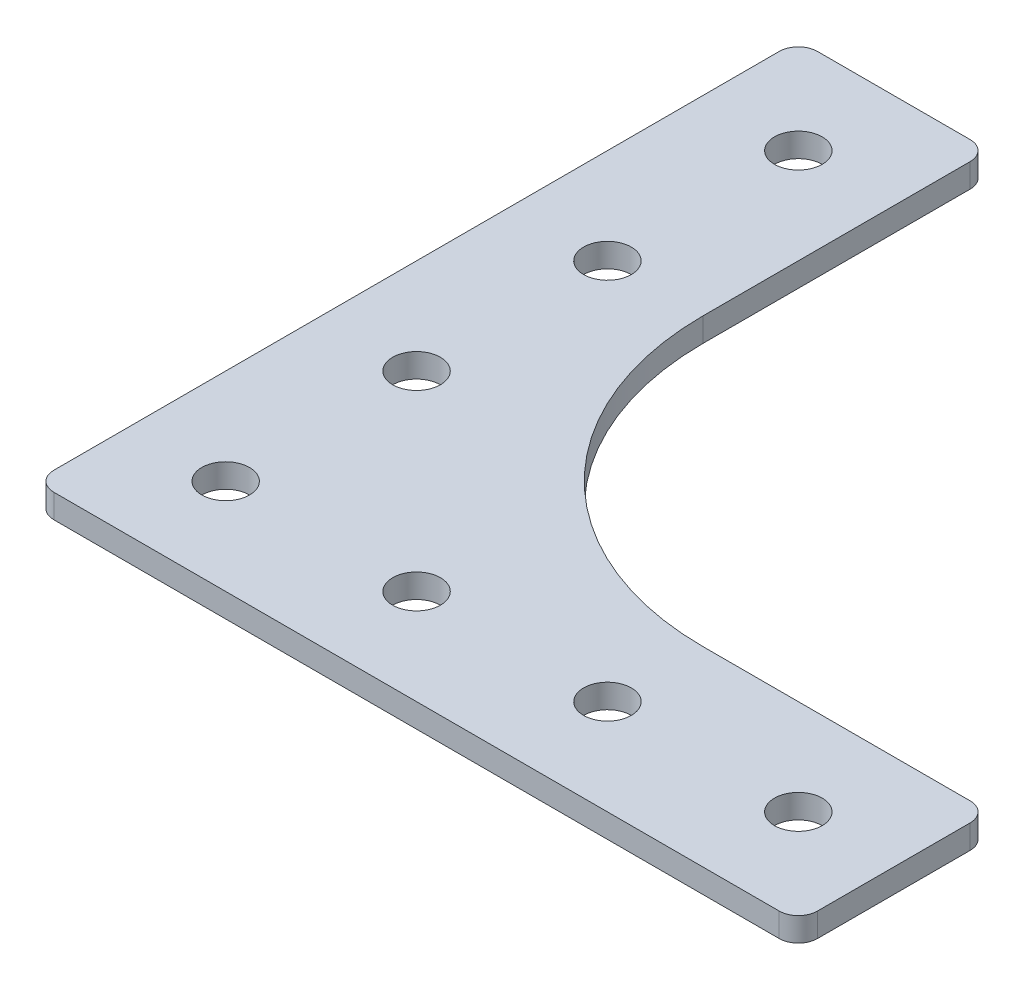
SolidWorks part; units mm, degrees
material "1060 Alloy"
ref_plane "Front Plane" through (0, 0, 0) normal (0, 0, 1) x (1, 0, 0)
ref_plane "Top Plane" through (0, 0, 0) normal (0, 1, 0) x (1, 0, 0)
ref_plane "Right Plane" through (0, 0, 0) normal (1, 0, 0) x (0, 0, -1)
sketch "Sketch2" plane through (0, 0, 0) normal (0, 1, 0) x (1, 0, 0)
  line L0 (-431.938, -442.7006) -> (-335.418, -442.7006)
  line L1 (277.4338, -442.7006) -> (-408.3662, -442.7006) construction
  line L2 (-434.478, -440.1606) -> (-434.478, -343.6406)
  line L3 (-434.478, -442.7006) -> (-434.478, 243.0994) construction
  line L4 (-431.938, -341.1006) -> (-411.618, -341.1006)
  line L5 (-409.078, -442.7006) -> (-409.078, 243.0994) construction
  line L6 (-332.878, -440.1606) -> (-332.878, -419.8406)
  line L7 (277.4338, -417.3006) -> (-408.3662, -417.3006) construction
  line L8 (-335.418, -417.3006) -> (-370.978, -417.3006)
  line L9 (-409.078, -379.2006) -> (-409.078, -343.6406)
  arc A0 (-411.618, -341.1006) -> (-409.078, -343.6406) centre (-411.618, -343.6406) cw
  arc A1 (-434.478, -343.6406) -> (-431.938, -341.1006) centre (-431.938, -343.6406) cw
  arc A2 (-431.938, -442.7006) -> (-434.478, -440.1606) centre (-431.938, -440.1606) cw
  arc A3 (-335.418, -442.7006) -> (-332.878, -440.1606) centre (-335.418, -440.1606) ccw
  arc A4 (-335.418, -417.3006) -> (-332.878, -419.8406) centre (-335.418, -419.8406) cw
  arc A5 (-409.078, -379.2006) -> (-370.978, -417.3006) centre (-370.978, -379.2006) ccw
  point P0 (-434.478, -442.7006)
  point P18 (-409.078, -341.1006)
  point P21 (-434.478, -341.1006)
  point P24 (-434.478, -442.7006)
  point P27 (-332.878, -442.7006)
  point P30 (-332.878, -417.3006)
  point P33 (-409.078, -417.3006)
  dimension "D1" = 2.54
  dimension "D2" = 2.54
  dimension "D3" = 2.54
  dimension "D4" = 2.54
  dimension "D5" = 2.54
  dimension "D6" = 38.1
extrude "Boss-Extrude1" add sketch "Sketch2" along normal blind 3.175
sketch "Sketch3" plane through (0, 3.175, 0) normal (0, 1, 0) x (1, 0, 0)
  line L0 (-421.778, -442.7006) -> (-421.778, -379.2006)
  line L1 (-431.938, -442.7006) -> (-335.418, -442.7006) construction
  line L2 (-421.778, -442.7006) -> (-421.778, -379.2006) construction
  line L3 (-421.778, -379.2006) -> (-421.778, -353.8006)
  line L4 (-345.1277, -430.0006) -> (-370.978, -430.0006)
  line L5 (-345.578, -430.0006) -> (-320.178, -430.0006) construction
  line L6 (-370.978, -430.0006) -> (-396.378, -430.0006)
  point P9 (-421.778, -404.6006)
  point P16 (-421.778, -430.0006)
hole_wizard "1/4 (0.25) Diameter Hole1" positions "Sketch4" profile "Sketch5" hole size "1/4" standard "ANSI Inch" end condition through all
sketch "Sketch4" plane through (0, 3.175, 0) normal (0, 1, 0) x (1, 0, 0)
  point P0 (-421.778, -353.8006)
  point P3 (-421.778, -379.2006)
  point P15 (-370.978, -430.0006)
  point P18 (-345.578, -430.0006)
sketch "Sketch5" plane through (-421.778, 3.175, 353.8006) normal (1, 0, 0) x (0, 0, 1)
  line L0 (0, 0) -> (0, 3.175)
  line L1 (0, 3.175) -> (3.175, 3.175)
  line L2 (3.175, 3.175) -> (3.175, 0)
  line L5 (3.175, 0) -> (0, 0)
  line L11 (0, -6.35) -> (0, 107.95) construction
  dimension "Thru Hole Dia." = 6.35
  dimension "Thru Hole Depth" = 3.175
hole_wizard "1/4 (0.25) Diameter Hole2" positions "Sketch6" profile "Sketch7" hole size "1/4" standard "ANSI Inch" end condition through all
sketch "Sketch6" plane through (0, 3.175, 0) normal (0, 1, 0) x (1, 0, 0)
  point P0 (-421.778, -430.0006)
  point P3 (-396.378, -430.0006)
  point P6 (-421.778, -404.6006)
sketch "Sketch7" plane through (-421.778, 3.175, 430.0006) normal (1, 0, 0) x (0, 0, 1)
  line L0 (0, 0) -> (0, 3.175)
  line L1 (0, 3.175) -> (3.175, 3.175)
  line L2 (3.175, 3.175) -> (3.175, 0)
  line L5 (3.175, 0) -> (0, 0)
  line L11 (0, -6.35) -> (0, 107.95) construction
  dimension "Thru Hole Dia." = 6.35
  dimension "Thru Hole Depth" = 3.175
